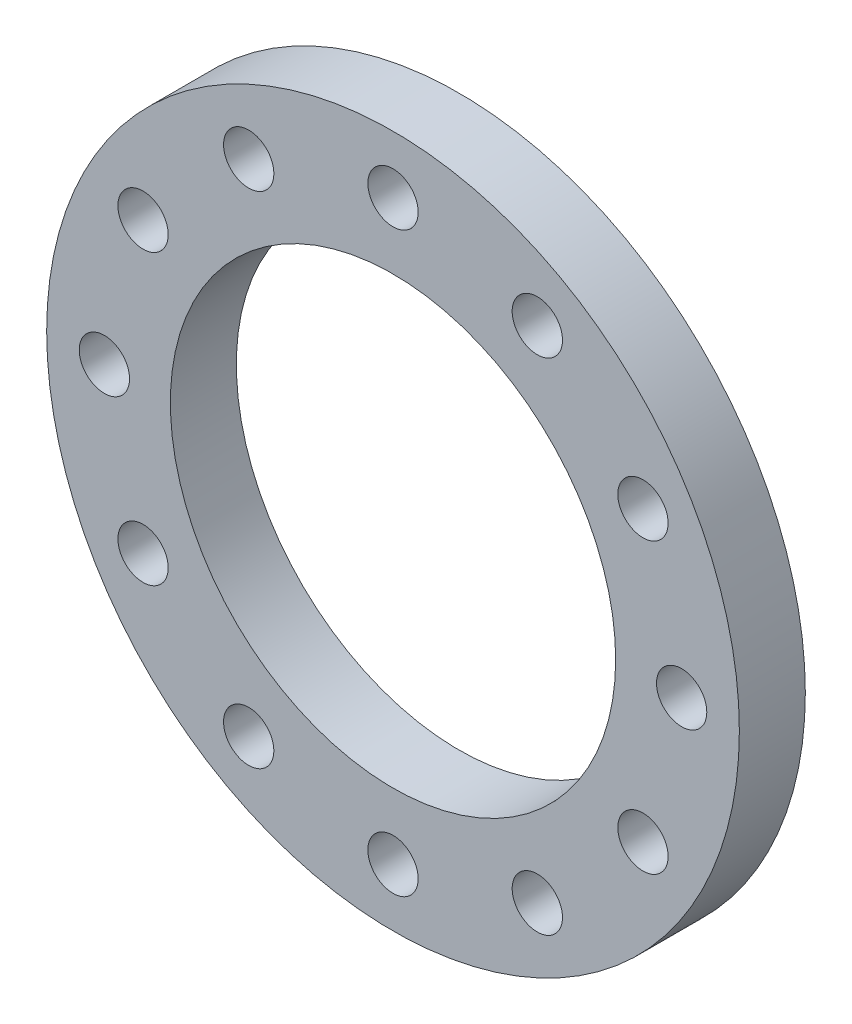
SolidWorks part; units mm, degrees
material "Thornel Mat VMA"
ref_plane "前视基准面" through (0, 0, 0) normal (0, 0, 1) x (1, 0, 0)
ref_plane "上视基准面" through (0, 0, 0) normal (0, 1, 0) x (1, 0, 0)
ref_plane "右视基准面" through (0, 0, 0) normal (1, 0, 0) x (0, 0, -1)
sketch "草图1" plane through (0, 0, 0) normal (0, 0, 1) x (1, 0, 0)
  line L0 (0, 0) -> (17.5, 0) construction
  circle A0 centre (0, 0) radius 21
  circle A1 centre (0, 0) radius 13.5
  circle A2 centre (0, 0) radius 17.5 construction
  circle A3 centre (0, 17.5) radius 1.525
  circle A4 centre (17.5, 0) radius 1.525
  circle A5 centre (0, -17.5) radius 1.525
  circle A6 centre (-17.5, 0) radius 1.525
  circle A7 centre (15.1554, -8.75) radius 1.525
  circle A8 centre (8.75, 15.1554) radius 1.525
  circle A9 centre (-15.1554, 8.75) radius 1.525
  circle A10 centre (-8.75, -15.1554) radius 1.525
  circle A11 centre (-15.1554, -8.75) radius 1.525
  circle A12 centre (8.75, -15.1554) radius 1.525
  circle A13 centre (15.1554, 8.75) radius 1.525
  circle A14 centre (-8.75, 15.1554) radius 1.525
  dimension "D1" = 42
  dimension "D2" = 27
  dimension "D3" = 35
  dimension "D4" = 3.05
  dimension "D6" = 17.5
  dimension "D5" = 3
extrude "凸台-拉伸1" add sketch "草图1" along normal blind 4
